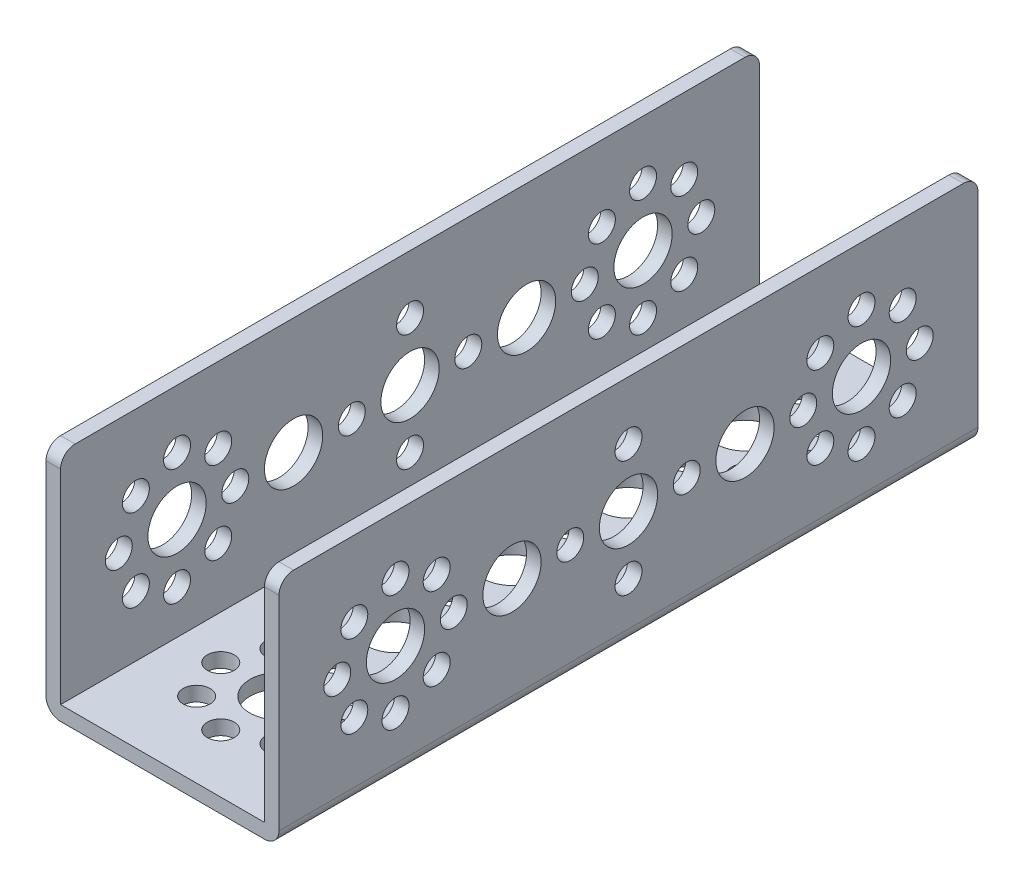
SolidWorks part; units mm, degrees
other "Defeature"
material "5052 Alloy"
ref_plane "Front Plane" through (0, 0, 0) normal (0, 0, 1) x (1, 0, 0)
ref_plane "Top Plane" through (0, 0, 0) normal (0, 1, 0) x (1, 0, 0)
ref_plane "Right Plane" through (0, 0, 0) normal (1, 0, 0) x (0, 0, -1)
sketch "Sketch1" plane through (0, 0, 0) normal (0, 0, 1) x (1, 0, 0)
  line L0 (-14, 0) -> (14, 0)
  line L1 (16, 2) -> (16, 32)
  line L2 (16, 32) -> (14, 32)
  line L3 (14, 32) -> (14, 2)
  line L4 (14, 2) -> (-14, 2)
  line L5 (-14, 2) -> (-14, 32)
  line L6 (-14, 32) -> (-16, 32)
  line L7 (-16, 32) -> (-16, 2)
  arc A0 (-16, 2) -> (-14, 0) centre (-14, 2) ccw
  arc A1 (16, 2) -> (14, 0) centre (14, 2) cw
  point P11 (0, 0)
  point P14 (16, 0)
  dimension "D7" = 2
  dimension "D1" = 32
  dimension "D2" = 2
  dimension "D3" = 2
  dimension "D4" = 2
  dimension "D5" = 32
  dimension "D6" = 32
extrude "Boss-Extrude1" add sketch "Sketch1" along normal mid plane 96
sketch "Sketch2" plane through (16, 0, 0) normal (1, 0, 0) x (0, 0, -1)
  line L1 (-48, 32) -> (48, 32) construction
  circle A0 centre (0, 16) radius 4
  circle A1 centre (8, 16) radius 1.85
  circle A2 centre (-8, 16) radius 1.85
  circle A3 centre (0, 8) radius 1.85
  circle A4 centre (0, 24) radius 1.85
  circle A5 centre (-16, 16) radius 4
  circle A6 centre (16, 16) radius 4
  circle A7 centre (0, 16) radius 8 construction
  point P5 (0, 32)
  circle B0 centre (40, 16) radius 1.85
  circle B1 centre (32, 8) radius 1.85
  circle B2 centre (32, 16) radius 4
  circle B3 centre (32, 24) radius 1.85
  circle B4 centre (26.3431, 21.6569) radius 1.85
  circle B5 centre (26.3431, 10.3431) radius 1.85
  circle B6 centre (24, 16) radius 1.85
  circle B7 centre (37.6569, 21.6569) radius 1.85
  circle B8 centre (37.6569, 10.3431) radius 1.85
  circle B9 centre (-24, 16) radius 1.85
  circle B10 centre (-32, 8) radius 1.85
  circle B11 centre (-32, 16) radius 4
  circle B12 centre (-32, 24) radius 1.85
  circle B13 centre (-37.6569, 21.6569) radius 1.85
  circle B14 centre (-37.6569, 10.3431) radius 1.85
  circle B15 centre (-40, 16) radius 1.85
  circle B16 centre (-26.3431, 21.6569) radius 1.85
  circle B17 centre (-26.3431, 10.3431) radius 1.85
  line B18 (-26.3431, 21.6569) -> (-37.6569, 10.3431) construction
  line B19 (-37.6569, 21.6569) -> (-26.3431, 10.3431) construction
  line B20 (-32, 16) -> (-32, 8) construction
  circle B21 centre (-32, 16) radius 8 construction
  dimension "D1" = 8
  dimension "D8" = 16
  dimension "D5" = 16
  dimension "D2" = 3.7
  dimension "D3" = 16
  dimension "D4" = 16
  dimension "D6" = 16
  dimension "D7" = 16
sketch_block_instance "Block2-3"
sketch_block "Block2" parameters "D1"=16.0089, "D2"=8, "D3"=3.7, "D4"=8
sketch_block_instance "Block2-4"
extrude "Cut-Extrude1" cut sketch "Sketch2" against normal blind 32
sketch "Sketch6" plane through (0, 2, 0) normal (0, 1, 0) x (1, 0, 0)
  line L0 (-14, -48) -> (-14, 48) construction
  line L1 (-14, 48) -> (14, 48) construction
  circle A0 centre (0, 0) radius 4
  circle A1 centre (0, 8) radius 1.85
  circle A2 centre (0, -8) radius 1.85
  circle A3 centre (8, 0) radius 1.85
  circle A4 centre (-8, 0) radius 1.85
  circle A5 centre (0, -16) radius 4
  circle A6 centre (0, 16) radius 4
  circle A7 centre (0, 0) radius 8 construction
  point P17 (-14, 0)
  point P20 (0, 48)
  circle B0 centre (0, 24) radius 1.85
  circle B1 centre (-8, 32) radius 1.85
  circle B2 centre (0, 32) radius 4
  circle B3 centre (8, 32) radius 1.85
  circle B4 centre (5.6569, 37.6569) radius 1.85
  circle B5 centre (-5.6569, 37.6569) radius 1.85
  circle B6 centre (0, 40) radius 1.85
  circle B7 centre (5.6569, 26.3431) radius 1.85
  circle B8 centre (-5.6569, 26.3431) radius 1.85
  circle B9 centre (0, -40) radius 1.85
  circle B10 centre (-8, -32) radius 1.85
  circle B11 centre (0, -32) radius 4
  circle B12 centre (8, -32) radius 1.85
  circle B13 centre (5.6569, -26.3431) radius 1.85
  circle B14 centre (-5.6569, -26.3431) radius 1.85
  circle B15 centre (0, -24) radius 1.85
  circle B16 centre (5.6569, -37.6569) radius 1.85
  circle B17 centre (-5.6569, -37.6569) radius 1.85
  dimension "D1" = 16
  dimension "D2" = 8
  dimension "D3" = 3.7
  dimension "D4" = 16
  dimension "D5" = 16
  dimension "D6" = 16
  dimension "D7" = 16
sketch_block_instance "Block2-5"
sketch_block_instance "Block2-6"
extrude "Cut-Extrude2" cut sketch "Sketch6" against normal blind 2
fillet "Fillet1" radius 2 4 edges at (-15, 32, 48) (-15, 32, -48) (15, 32, -48) (15, 32, 48)
